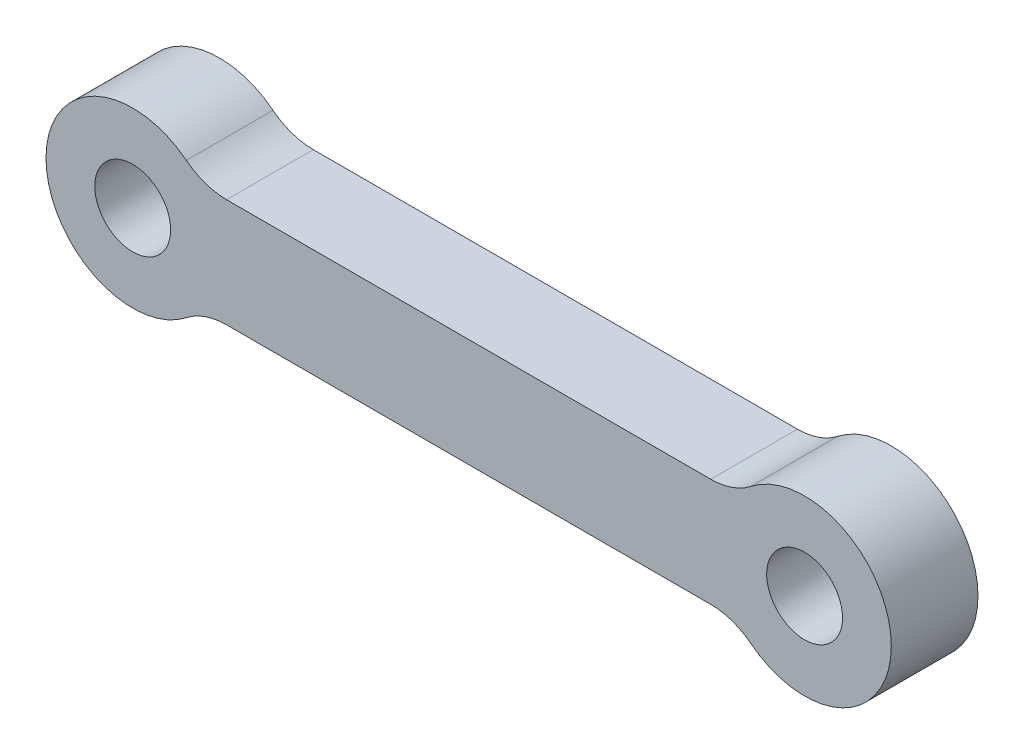
SolidWorks part; units mm, degrees
material "Acrylic (Medium-high impact)"
ref_plane "Front Plane" through (0, 0, 0) normal (0, 0, 1) x (1, 0, 0)
ref_plane "Top Plane" through (0, 0, 0) normal (0, 1, 0) x (1, 0, 0)
ref_plane "Right Plane" through (0, 0, 0) normal (1, 0, 0) x (0, 0, -1)
sketch "Sketch1" plane through (0, 0, 0) normal (0, 0, 1) x (1, 0, 0)
  line L0 (-15.5, 0) -> (15.5, 0) construction
  line L1 (0, 2.5) -> (0, -2.5) construction
  line L2 (-12.3775, 2.5) -> (12.3775, 2.5)
  line L3 (-12.3775, -2.5) -> (12.3775, -2.5)
  circle A0 centre (15.5, 0) radius 1.75
  circle A1 centre (15.5, 0) radius 4
  circle A2 centre (-15.5, 0) radius 1.75
  circle A3 centre (-15.5, 0) radius 4
  point P4 (0, 0)
  dimension "D2" = 3.5
  dimension "D3" = 8
  dimension "D1" = 31
  dimension "D4" = 5
extrude "Boss-Extrude1" add sketch "Sketch1" along normal blind 4 contours A3 A2 | L2 A3 L3 A1 | A1 A0
fillet "Fillet1" radius 3 4 edges at (12.3775, -2.5, 2) (-12.3775, -2.5, 2) (12.3775, 2.5, 2) (-12.3775, 2.5, 2)
